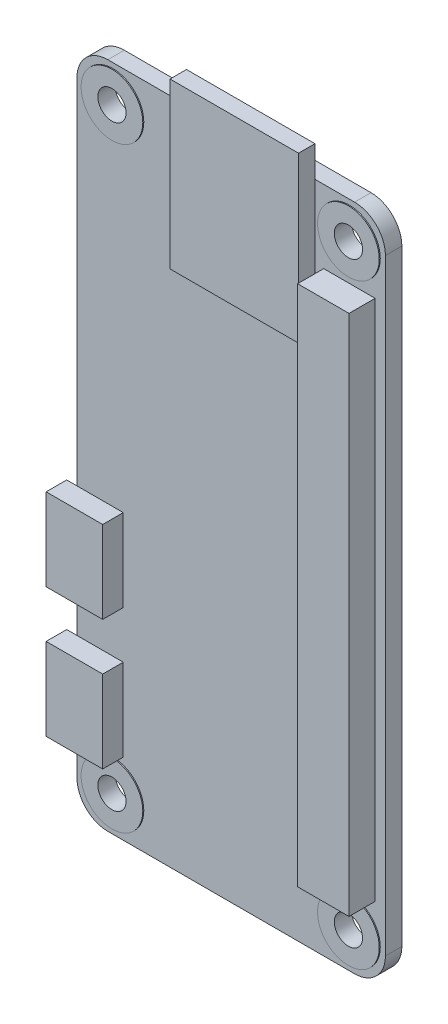
SolidWorks part; units mm, degrees
ref_plane "Front Plane" through (0, 0, 0) normal (0, 0, 1) x (1, 0, 0)
ref_plane "Top Plane" through (0, 0, 0) normal (0, 1, 0) x (1, 0, 0)
ref_plane "Right Plane" through (0, 0, 0) normal (1, 0, 0) x (0, 0, -1)
sketch "Sketch1" plane through (0, 0, 0) normal (0, 0, 1) x (1, 0, 0)
  line L1 (-11.5, -29) -> (11.5, -29) construction
  line L2 (-11.5, -29) -> (-11.5, 29) construction
  line L3 (-11.5, 29) -> (11.5, 29) construction
  line L4 (11.5, -29) -> (11.5, 29) construction
  line L5 (-11.5, -29) -> (11.5, 29) construction
  line L6 (-11.5, 29) -> (11.5, -29) construction
  line L7 (-15, -32.5) -> (15, -32.5)
  line L8 (-15, -32.5) -> (-15, 32.5)
  line L9 (-15, 32.5) -> (15, 32.5)
  line L10 (15, -32.5) -> (15, 32.5)
  line L11 (-15, -32.5) -> (15, 32.5) construction
  line L12 (-15, 32.5) -> (15, -32.5) construction
  circle A0 centre (-11.5, 29) radius 1.375
  circle A1 centre (11.5, 29) radius 1.375
  circle A2 centre (-11.5, -29) radius 1.375
  circle A3 centre (11.5, -29) radius 1.375
  point P0 (0, 0)
  point P5 (0, 0)
  dimension "D1" = 2.75
  dimension "D2" = 23
  dimension "D3" = 58
  dimension "D4" = 3.5
  dimension "D5" = 3.5
extrude "Boss-Extrude1" add sketch "Sketch1" along normal mid plane 1.6 contours L7 L10 L9 L8 A3 A2 A1 A0
sketch "Sketch4" plane through (0, 0, 0.8) normal (0, 0, 1) x (1, 0, 0)
  circle A0 centre (11.5, 29) radius 1.375 construction
  circle A1 centre (11.5, -29) radius 1.375 construction
  circle A2 centre (-11.5, -29) radius 1.375 construction
  circle A3 centre (-11.5, 29) radius 1.375 construction
  circle A4 centre (11.5, 29) radius 1.375
  circle A5 centre (11.5, -29) radius 1.375
  circle A6 centre (-11.5, -29) radius 1.375
  circle A7 centre (-11.5, 29) radius 1.375
extrude "Extrude-Thin1" add sketch "Sketch4" along normal blind 0.1 thin
fillet "Fillet1" radius 3 4 edges at (-15, -32.5, 0) (-15, 32.5, 0) (15, -32.5, 0) (15, 32.5, 0)
sketch "Sketch2" plane through (0, 0, 0.8) normal (0, 0, 1) x (1, 0, 0)
  line L0 (-15, -29.5) -> (-15, 29.5) construction
  line L1 (-12, 32.5) -> (12, 32.5) construction
  line L2 (-4.35, 19.5) -> (8.15, 19.5)
  line L3 (-4.35, 19.5) -> (-4.35, 35.5)
  line L4 (-4.35, 35.5) -> (8.15, 35.5)
  line L5 (8.15, 19.5) -> (8.15, 35.5)
  line L6 (-4.35, 19.5) -> (8.15, 35.5) construction
  line L7 (-4.35, 35.5) -> (8.15, 19.5) construction
  point P0 (1.9, 27.5)
  dimension "D1" = 12.5
  dimension "D2" = 16.9
  dimension "D3" = 3
  dimension "D4" = 16
extrude "Boss-Extrude2" add sketch "Sketch2" along normal blind 1.6
sketch "Sketch3" plane through (0, 0, 0.8) normal (0, 0, 1) x (1, 0, 0)
  line L0 (15, -29.5) -> (15, 29.5) construction
  line L1 (14, -25.4) -> (9, -25.4)
  line L2 (14, -25.4) -> (14, 25.4)
  line L3 (14, 25.4) -> (9, 25.4)
  line L4 (9, -25.4) -> (9, 25.4)
  line L5 (14, -25.4) -> (9, 25.4) construction
  line L6 (14, 25.4) -> (9, -25.4) construction
  line L7 (0, 0) -> (11.5, 0) construction
  point P0 (11.5, 0)
  dimension "D1" = 3.5
  dimension "D2" = 5
  dimension "D3" = 50.8
extrude "Boss-Extrude3" add sketch "Sketch3" along normal blind 2.54
sketch "Sketch5" plane through (0, 0, 0.8) normal (0, 0, 1) x (1, 0, 0)
  line L0 (-16, -25.5) -> (-10.5, -25.5)
  line L1 (-16, -12.9) -> (-10.5, -12.9)
  line L2 (-16, -12.9) -> (-16, -4.9)
  line L3 (-16, -4.9) -> (-10.5, -4.9)
  line L4 (-10.5, -12.9) -> (-10.5, -4.9)
  line L5 (-16, -12.9) -> (-10.5, -4.9) construction
  line L6 (-16, -4.9) -> (-10.5, -12.9) construction
  line L7 (-16, -25.5) -> (-16, -17.5)
  line L8 (-16, -17.5) -> (-10.5, -17.5)
  line L9 (-10.5, -25.5) -> (-10.5, -17.5)
  line L10 (-16, -25.5) -> (-10.5, -17.5) construction
  line L11 (-16, -17.5) -> (-10.5, -25.5) construction
  line L12 (-12, 32.5) -> (-4.35, 32.5) construction
  line L13 (-15, -29.5) -> (-15, 29.5) construction
  point P0 (-13.25, -8.9)
  point P7 (-13.25, -21.5)
  dimension "D1" = 2
  dimension "D2" = 41.4
  dimension "D3" = 1
  dimension "D4" = 5.5
  dimension "D5" = 8
  dimension "D6" = 12.6
extrude "Boss-Extrude4" add sketch "Sketch5" along normal blind 2
